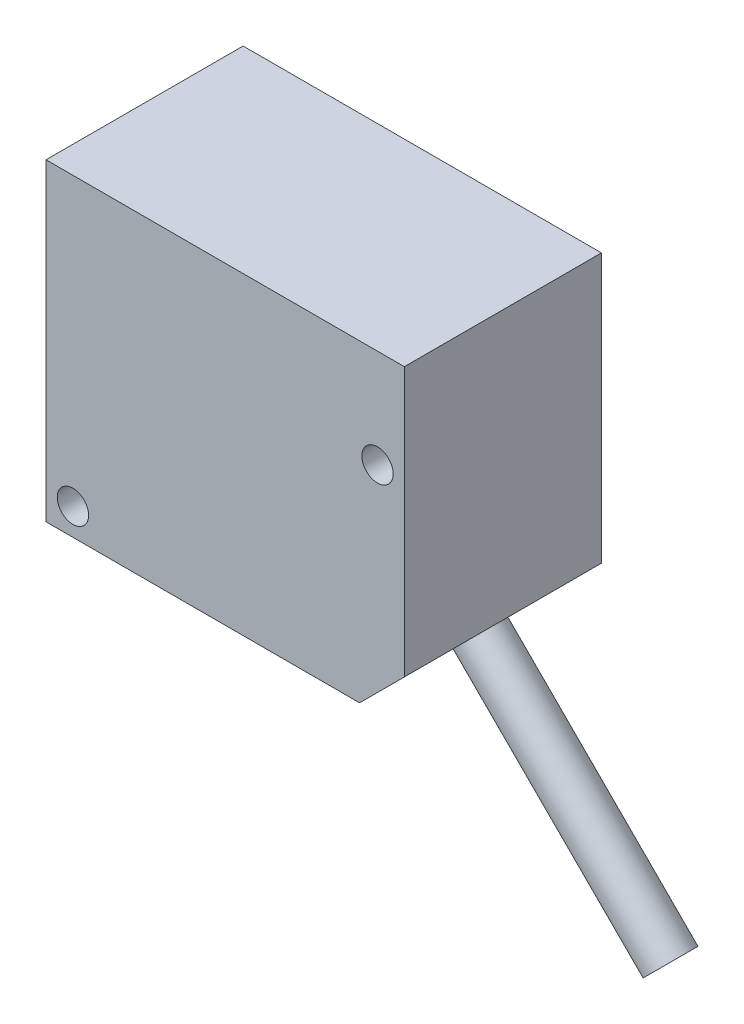
SolidWorks part; units mm, degrees
ref_plane "前视基准面" through (0, 0, 0) normal (0, 0, 1) x (1, 0, 0)
ref_plane "上视基准面" through (0, 0, 0) normal (0, 1, 0) x (1, 0, 0)
ref_plane "右视基准面" through (0, 0, 0) normal (1, 0, 0) x (0, 0, -1)
sketch "草图1" plane through (0, 0, 0) normal (0, 0, 1) x (1, 0, 0)
  line L1 (20, 17.5) -> (-20, 17.5)
  line L2 (20, 17.5) -> (20, -17.5)
  line L3 (20, -17.5) -> (-20, -17.5)
  line L4 (-20, 17.5) -> (-20, -17.5)
  line L5 (20, 17.5) -> (-20, -17.5) construction
  line L6 (20, -17.5) -> (-20, 17.5) construction
  point P0 (0, 0)
  dimension "D1" = 40
  dimension "D2" = 35
extrude "凸台-拉伸1" add sketch "草图1" along normal blind 22
sketch "草图2" plane through (0, 0, 22) normal (0, 0, 1) x (1, 0, 0)
  line L1 (-20, -17.5) -> (20, -17.5) construction
  line L2 (20, -17.5) -> (20, 17.5) construction
  circle A0 centre (17, 6.5) radius 1.75
  circle A1 centre (-17, -14.5) radius 1.75
  dimension "D1" = 3.5
  dimension "D3" = 3
  dimension "D4" = 24
  dimension "D5" = 3
  dimension "D2" = 37
extrude "切除-拉伸1" cut sketch "草图2" against normal through all
chamfer "倒角1" distance 5 angle 45 1 edges at (20, -17.5, 11)
sketch "草图3" plane through (16.25, -16.25, 0) normal (0.7071, -0.7071, 0) x (0, 0, -1)
  line L0 (-22, 1.7678) -> (0, 1.7678) construction
  line L1 (-22, -1.7678) -> (-22, 5.3033) construction
  line L2 (0, 5.3033) -> (0, -1.7678) construction
  circle A0 centre (-11, 1.7678) radius 2.5
  dimension "D1" = 5
extrude "凸台-拉伸2" add sketch "草图3" along normal blind 30
sketch "草图4" plane through (-20, 0, 0) normal (-1, 0, 0) x (0, 0, 1)
  line L0 (11, 17.5) -> (11, -17.5) construction
  line L1 (3.7882, 13.2707) -> (18.2118, 13.2707)
  line L2 (3.7882, 13.2707) -> (3.7882, -13.2707)
  line L3 (3.7882, -13.2707) -> (18.2118, -13.2707)
  line L4 (18.2118, 13.2707) -> (18.2118, -13.2707)
  line L5 (3.7882, 13.2707) -> (18.2118, -13.2707) construction
  line L6 (3.7882, -13.2707) -> (18.2118, 13.2707) construction
  line L7 (22, 17.5) -> (0, 17.5) construction
  line L8 (22, -17.5) -> (0, -17.5) construction
  line L9 (0, 0) -> (22, 0) construction
  line L10 (22, 17.5) -> (22, -17.5) construction
  point P0 (11, 0)
extrude "切除-拉伸2" cut sketch "草图4" against normal blind 0.1
